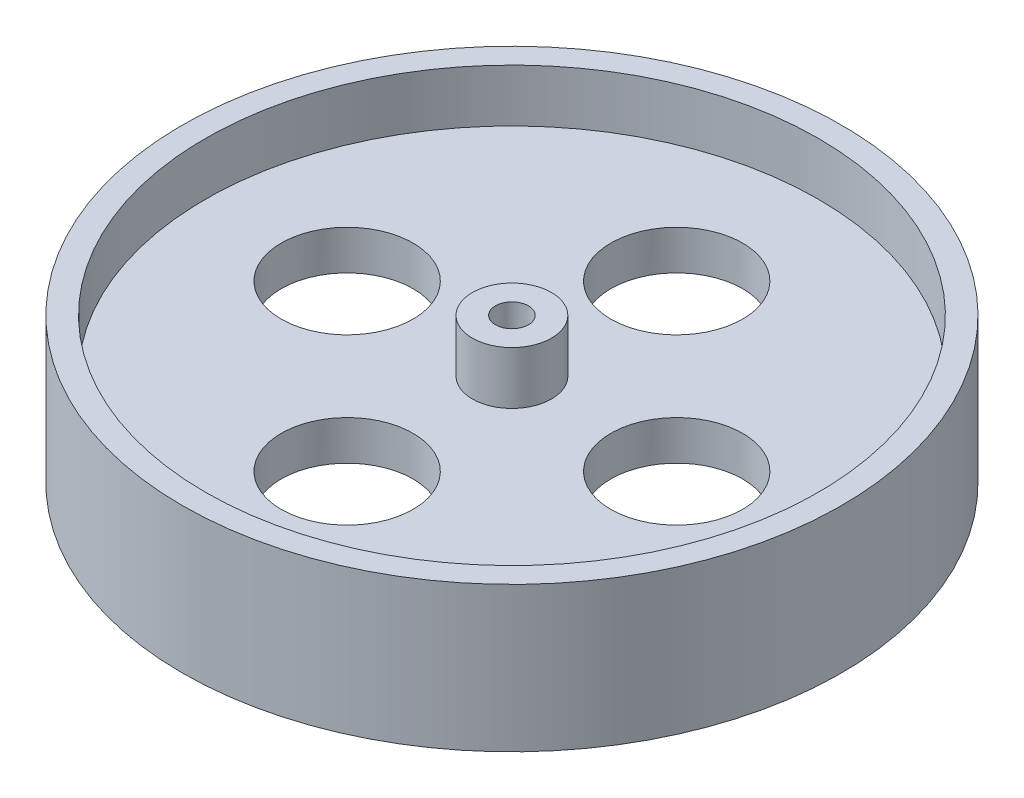
SolidWorks part; units mm, degrees
ref_plane "Plan de face" through (0, 0, 0) normal (0, 0, 1) x (1, 0, 0)
ref_plane "Plan de dessus" through (0, 0, 0) normal (0, 1, 0) x (1, 0, 0)
ref_plane "Plan de droite" through (0, 0, 0) normal (1, 0, 0) x (0, 0, -1)
sketch "Esquisse1" plane through (0, 0, 0) normal (0, 1, 0) x (1, 0, 0)
  circle A0 centre (0, 0) radius 50
extrude "Boss.-Extru.1" add sketch "Esquisse1" along normal blind 22
sketch "Esquisse2" plane through (0, 22, 0) normal (0, 1, 0) x (1, 0, 0)
  circle A0 centre (0, 0) radius 2.5
extrude "Enlèv. mat.-Extru.1" cut sketch "Esquisse2" against normal blind 7
sketch "Esquisse3" plane through (0, 0, 0) normal (0, -1, 0) x (-1, 0, 0)
  line L0 (2.1703, -1.2408) -> (2.4157, 0.6437)
  circle A0 centre (0, 0) radius 2.5
extrude "Enlèv. mat.-Extru.3" cut sketch "Esquisse3" against normal blind 15 contours L0 A0
sketch "Esquisse4" plane through (0, 22, 0) normal (0, 1, 0) x (1, 0, 0)
  circle A0 centre (0, 0) radius 6
  circle A1 centre (0, 0) radius 46.5
extrude "Enlèv. mat.-Extru.4" cut sketch "Esquisse4" against normal blind 8
sketch "Esquisse5" plane through (0, 0, 0) normal (0, -1, 0) x (-1, 0, 0)
  circle A0 centre (0, 0) radius 6
  circle A1 centre (0, 0) radius 46.5
extrude "Enlèv. mat.-Extru.5" cut sketch "Esquisse5" against normal blind 8
sketch "Esquisse6" plane through (0, 14, 0) normal (0, 1, 0) x (1, 0, 0)
  circle A0 centre (0, 25) radius 10
extrude "Enlèv. mat.-Extru.6" cut sketch "Esquisse6" against normal blind 8
sketch "Esquisse7" plane through (0, 14, 0) normal (0, 1, 0) x (1, 0, 0)
  circle A0 centre (25, 0) radius 10
extrude "Enlèv. mat.-Extru.7" cut sketch "Esquisse7" against normal blind 8
sketch "Esquisse8" plane through (0, 14, 0) normal (0, 1, 0) x (1, 0, 0)
  circle A0 centre (0, -25) radius 10
extrude "Enlèv. mat.-Extru.8" cut sketch "Esquisse8" against normal blind 8
sketch "Esquisse9" plane through (0, 14, 0) normal (0, 1, 0) x (1, 0, 0)
  circle A0 centre (-25, 0) radius 10
extrude "Enlèv. mat.-Extru.9" cut sketch "Esquisse9" against normal blind 8
